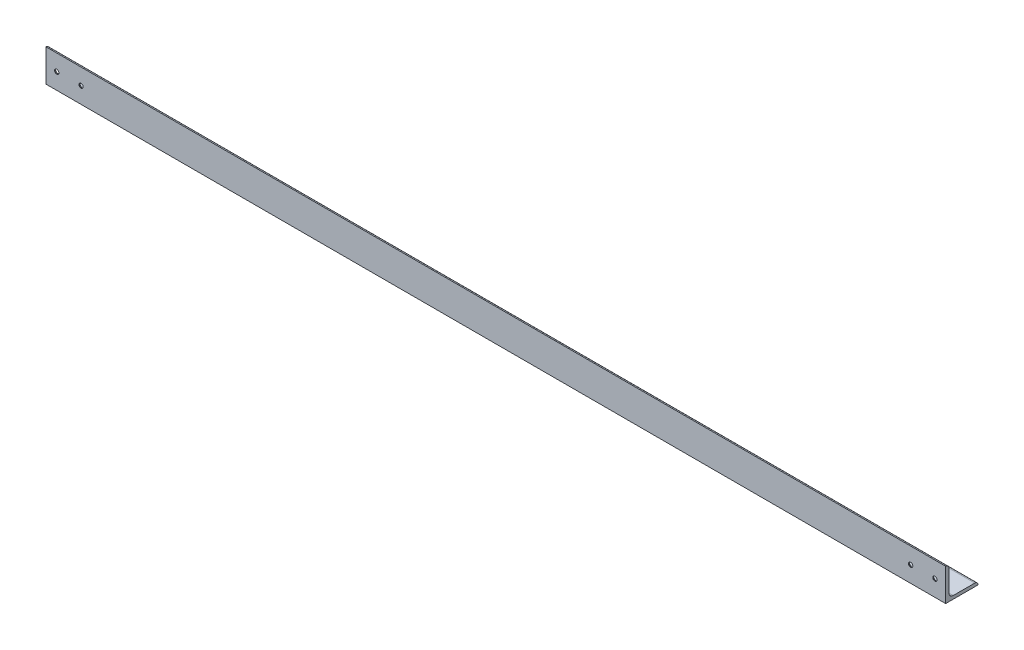
SolidWorks part; units mm, degrees
ref_plane "Front Plane" through (0, 0, 0) normal (0, 0, 1) x (1, 0, 0)
ref_plane "Top Plane" through (0, 0, 0) normal (0, 1, 0) x (1, 0, 0)
ref_plane "Right Plane" through (0, 0, 0) normal (1, 0, 0) x (0, 0, -1)
sketch "Sketch1" plane through (0, 0, 0) normal (0, 1, 0) x (1, 0, 0)
  line L0 (0, 0) -> (1670, 0)
  dimension "D1" = 1670
other "L angle (equal) 60X60X6(6)"
ref_plane "Plane1" through (0, 0, 0) normal (1, 0, 0) x (0, 0, -1)
sketch "Sketch17" plane through (0, 0, 0) normal (1, 0, 0) x (0, 0, -1)
  line L0 (0, 60) -> (0, 0)
  line L2 (6, 54) -> (6, 14)
  line L3 (14, 6) -> (54, 6)
  line L5 (60, 0) -> (0, 0)
  arc A0 (6, 54) -> (0, 60) centre (0, 54) ccw
  arc A1 (60, 0) -> (54, 6) centre (54, 0) ccw
  arc A2 (14, 6) -> (6, 14) centre (14, 14) cw
  point P8 (0, 30)
  point P9 (30, 0)
  point P10 (0, 0)
  dimension "Radius_2" = 6
  dimension "Radius_1" = 8
  dimension "V_leg" = 60
  dimension "H_leg" = 60
  dimension "thickness" = 6
sketch "Sketch14" plane through (0, 0, 0) normal (0, 0, 1) x (1, 0, 0)
  line L5 (940, 30) -> (940, 0) construction
  line L7 (0, 60) -> (0, 0) construction
  line L13 (0, 60) -> (0, 0)
  line L14 (0, 0) -> (1670, 0)
  line L15 (1670, 0) -> (1670, 60)
  line L16 (1670, 60) -> (0, 60)
  line L18 (0, 0) -> (420, 0) construction
  line L21 (1670, 60) -> (1670, 0) construction
  line L26 (420, 60) -> (0, 60) construction
  circle A0 centre (65, 30) radius 4
  circle A1 centre (1605, 30) radius 4
  circle A2 centre (1650, 30) radius 4
  circle A4 centre (20, 30) radius 4
  circle A5 centre (1560, 30) radius 4 [skipped]
  point P9 (940, 15)
  dimension "D3" = 20
  dimension "D5" = 2
  dimension "D2" = 20
  dimension "D7" = 45
  dimension "D1" = 0
  dimension "D4" = 2
extrude "Cut-Extrude1" cut sketch "Sketch14" against normal through all
chamfer "Chamfer1" distance 5.5 angle 45 4 edges at (69, 30, -6) (1609, 30, -6) (1654, 30, -6) (24, 30, -6)
ref_plane "Plane2" through (0, 0, 0) normal (0, -1, 0) x (-1, 0, 0)
sketch "Sketch18" plane through (0, 0, 0) normal (0, -1, 0) x (-1, 0, 0)
  line L0 (0, 0) -> (0, 60) construction
  line L4 (-35, 30) -> (-235, 30) construction
  line L7 (-35, 60) -> (-35, 0) construction
  circle A4 centre (-35, 30) radius 4
  dimension "D5" = 200
  dimension "D2" = 35
extrude "Cut-Extrude2" cut sketch "Sketch18" against normal through all
pattern_linear "LPattern1" count 5 spacing 400 along (1, 0, 0) count 5 spacing 400 along (0, -1, 0) of "Cut-Extrude2"
